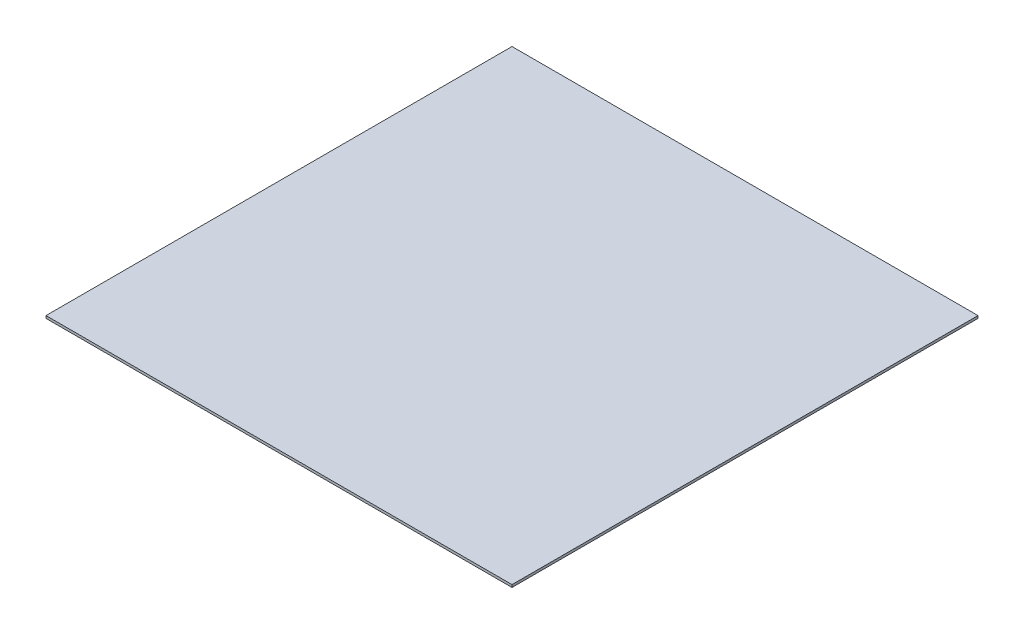
SolidWorks part; units mm, degrees
ref_plane "Front Plane" through (0, 0, 0) normal (0, 0, 1) x (1, 0, 0)
ref_plane "Top Plane" through (0, 0, 0) normal (0, 1, 0) x (1, 0, 0)
ref_plane "Right Plane" through (0, 0, 0) normal (1, 0, 0) x (0, 0, -1)
sketch "Sketch1" plane through (0, 0, 0) normal (0, 1, 0) x (1, 0, 0)
  line L1 (-750, -750) -> (750, -750)
  line L2 (-750, -750) -> (-750, 750)
  line L3 (-750, 750) -> (750, 750)
  line L4 (750, -750) -> (750, 750)
  line L5 (-750, -750) -> (750, 750) construction
  line L6 (-750, 750) -> (750, -750) construction
  point P0 (0, 0)
  dimension "D1" = 1500
  dimension "D2" = 1500
extrude "Boss-Extrude1" add sketch "Sketch1" along normal blind 8
